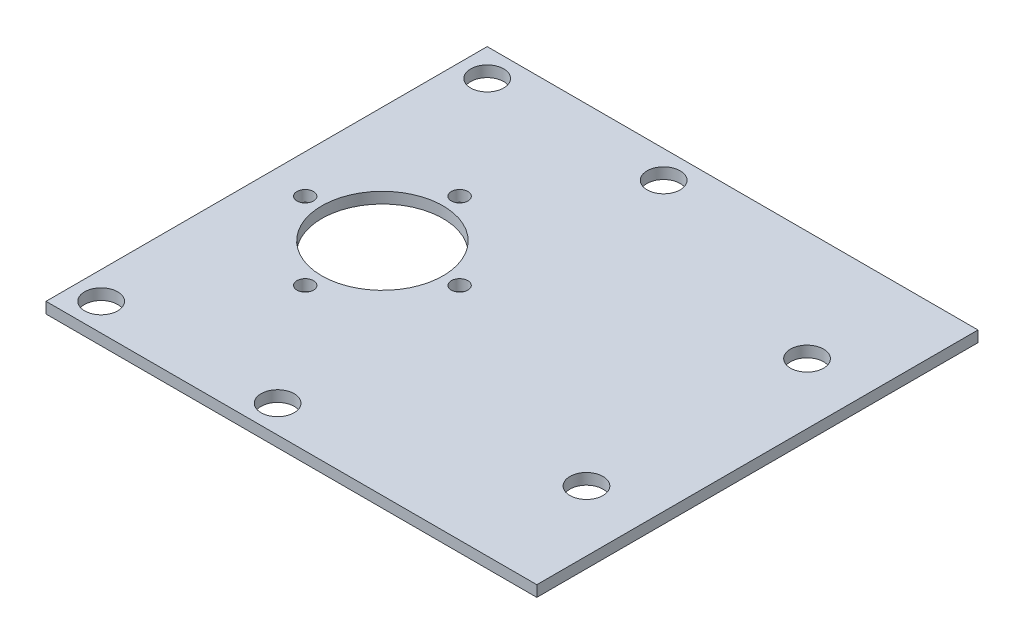
SolidWorks part; units mm, degrees
ref_plane "Plan de face" through (0, 0, 0) normal (0, 0, 1) x (1, 0, 0)
ref_plane "Plan de dessus" through (0, 0, 0) normal (0, 1, 0) x (1, 0, 0)
ref_plane "Plan de droite" through (0, 0, 0) normal (1, 0, 0) x (0, 0, -1)
sketch "Esquisse1" plane through (0, 0, 0) normal (0, 1, 0) x (1, 0, 0)
  line L1 (0, 0) -> (89, 0)
  line L2 (0, 0) -> (0, 80)
  line L3 (0, 80) -> (89, 80)
  line L4 (89, 0) -> (89, 80)
  dimension "D1" = 80
  dimension "D2" = 89
extrude "Extrusion1" add sketch "Esquisse1" along normal blind 2
sketch "Esquisse2" plane through (0, 2, 0) normal (0, 1, 0) x (1, 0, 0)
  line L0 (0, 80) -> (0, 0) construction
  line L1 (0, 0) -> (89, 0) construction
  circle A0 centre (21, 40) radius 11
  dimension "D1" = 22
  dimension "D3" = 40
  dimension "D2" = 21
sketch "Esquisse4" plane through (0, 2, 0) normal (0, 1, 0) x (-1, 0, 0)
  line L0 (-89, -80) -> (0, -80) construction
  line L1 (0, -80) -> (0, 0) construction
  line L2 (-89, 0) -> (-89, -80) construction
  circle A0 centre (-35, -40) radius 1.5
  circle A1 centre (-21, -26) radius 1.5
  circle A2 centre (-7, -40) radius 1.5
  circle A3 centre (-21, -54) radius 1.5
  circle A4 centre (-5, -75) radius 3
  circle A5 centre (-5, -5) radius 3
  circle A6 centre (-37, -5) radius 3
  circle A7 centre (-37, -75) radius 3
  circle A8 centre (-78, -60) radius 3
  circle A9 centre (-78, -20) radius 3
  dimension "D1" = 14
  dimension "D2" = 6
  dimension "D3" = 5
  dimension "D4" = 5
  dimension "D5" = 6
  dimension "D6" = 20
  dimension "D7" = 11
extrude "Extrusion3" cut sketch "Esquisse2" against normal through all
extrude "Extrusion4" cut sketch "Esquisse4" against normal through all
